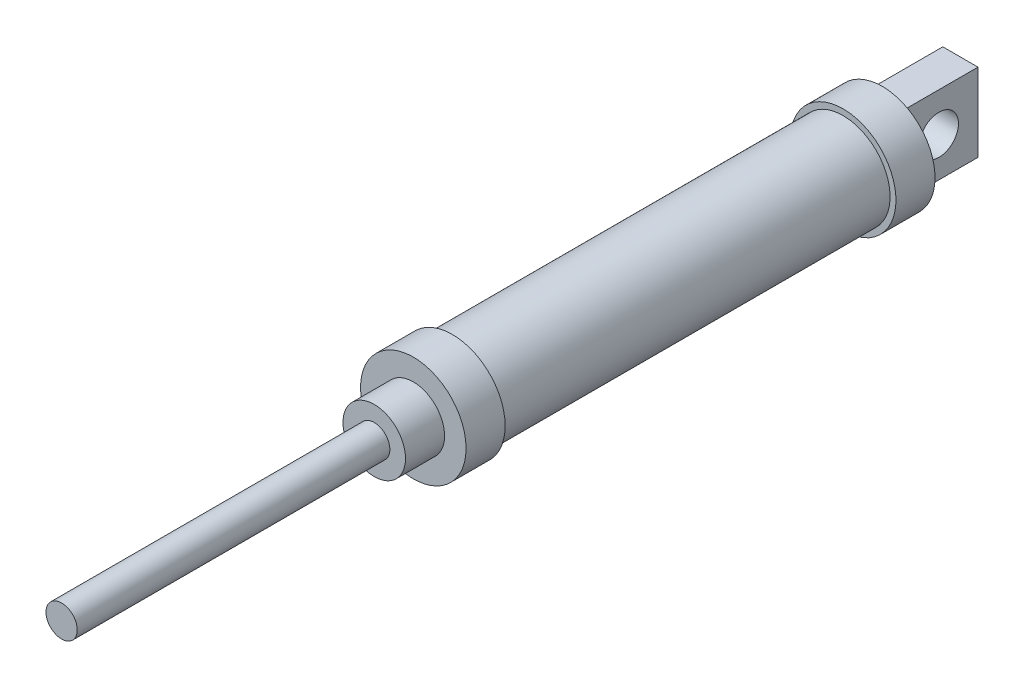
SolidWorks part; units mm, degrees
ref_plane "Front Plane" through (0, 0, 0) normal (0, 0, 1) x (1, 0, 0)
ref_plane "Top Plane" through (0, 0, 0) normal (0, 1, 0) x (1, 0, 0)
ref_plane "Right Plane" through (0, 0, 0) normal (1, 0, 0) x (0, 0, -1)
sketch "Sketch1" plane through (0, 0, 0) normal (0, 0, 1) x (1, 0, 0)
  circle A0 centre (0, 0) radius 13.5
  dimension "D1" = 27
extrude "Boss-Extrude1" add sketch "Sketch1" along normal blind 10
sketch "Sketch2" plane through (0, 0, 10) normal (0, 0, 1) x (1, 0, 0)
  circle A0 centre (0, 0) radius 8
  dimension "D1" = 16
extrude "Boss-Extrude2" add sketch "Sketch2" along normal blind 10
sketch "Sketch3" plane through (0, 0, 0) normal (0, 0, -1) x (-1, 0, 0)
  circle A0 centre (0, 0) radius 12
  dimension "D1" = 24
extrude "Boss-Extrude3" add sketch "Sketch3" along normal blind 100
sketch "Sketch4" plane through (0, 0, -100) normal (0, 0, -1) x (-1, 0, 0)
  circle A0 centre (0, 0) radius 13.5
  dimension "D1" = 27
extrude "Boss-Extrude4" add sketch "Sketch4" along normal blind 10 contours A0
sketch "Sketch5" plane through (0, 0, -110) normal (0, 0, -1) x (-1, 0, 0)
  line L1 (4.5, -10) -> (-4.5, -10)
  line L2 (4.5, -10) -> (4.5, 10)
  line L3 (4.5, 10) -> (-4.5, 10)
  line L4 (-4.5, -10) -> (-4.5, 10)
  line L5 (4.5, -10) -> (-4.5, 10) construction
  line L6 (4.5, 10) -> (-4.5, -10) construction
  point P0 (0, 0)
  dimension "D1" = 9
  dimension "D2" = 20
extrude "Boss-Extrude5" add sketch "Sketch5" along normal blind 20
sketch "Sketch6" plane through (4.5, 0, 0) normal (1, 0, 0) x (0, 0, -1)
  line L0 (110, 10) -> (130, -10) construction
  line L1 (130, -10) -> (110, -10) construction
  line L2 (130, -10) -> (130, 10) construction
  line L3 (130, 10) -> (110, -10) construction
  circle A0 centre (120, 0) radius 5
  dimension "D1" = 10
extrude "Cut-Extrude1" cut sketch "Sketch6" against normal blind 20 contours A0
sketch "Sketch8" plane through (0, 0, 20) normal (0, 0, 1) x (1, 0, 0)
  circle A0 centre (0, 0) radius 4
  dimension "D1" = 8
extrude "Boss-Extrude6" add sketch "Sketch8" along normal blind 80
